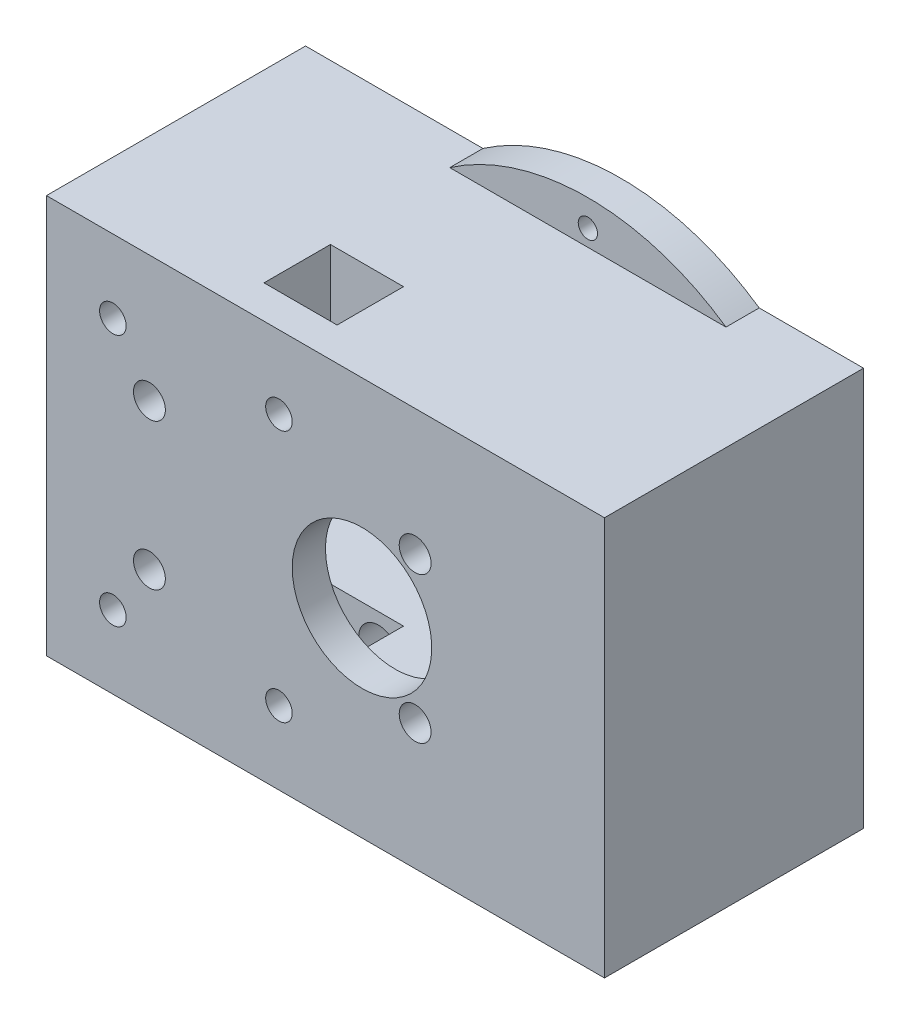
SolidWorks part; units mm, degrees
ref_plane "前视基准面" through (0, 0, 0) normal (0, 0, 1) x (1, 0, 0)
ref_plane "上视基准面" through (0, 0, 0) normal (0, 1, 0) x (1, 0, 0)
ref_plane "右视基准面" through (0, 0, 0) normal (1, 0, 0) x (0, 0, -1)
sketch "草图1" plane through (0, 0, 0) normal (0, 0, 1) x (1, 0, 0)
  line L1 (-33.4499, 20.5621) -> (50.5501, 20.5621)
  line L2 (-33.4499, 20.5621) -> (-33.4499, -39.4379)
  line L3 (-33.4499, -39.4379) -> (50.5501, -39.4379)
  line L4 (50.5501, 20.5621) -> (50.5501, -39.4379)
  dimension "D1" = 84
  dimension "D2" = 60
extrude "凸台-拉伸1" add sketch "草图1" along normal blind 39
sketch "草图3" plane through (0, 0, 0) normal (0, 0, -1) x (-1, 0, 0)
  line L1 (-50.5501, -39.4379) -> (-50.5501, 20.5621) construction
  line L2 (33.4499, -39.4379) -> (-50.5501, -39.4379) construction
  circle A0 centre (-14.0501, -9.4379) radius 36.5
  point P2 (-21.5499, -29.1391)
  dimension "D1" = 36.5
  dimension "D2" = 30
extrude "凸台-拉伸2" add sketch "草图3" against normal blind 5
sketch "草图4" plane through (0, 0, 0) normal (0, 0, -1) x (-1, 0, 0)
  line L0 (-50.5501, -39.4379) -> (-50.5501, 20.5621) construction
  line L1 (-34.8408, -39.4379) -> (-50.5501, -39.4379) construction
  circle A0 centre (-46.5501, -9.4379) radius 1.45
  dimension "D1" = 2.9
  dimension "D2" = 4
  dimension "D3" = 30
extrude "切除-拉伸2" cut sketch "草图4" against normal blind 5
pattern_circular "阵列(圆周)1" count 8 over 360 about axis through (14.0501, -9.4379, 0) along (0, 0, 1) of "切除-拉伸2"
sketch "草图2" plane through (0, 0, 0) normal (0, 0, -1) x (-1, 0, 0)
  line L0 (33.4499, 20.5621) -> (33.4499, -39.4379) construction
  line L1 (33.4499, 4.8121) -> (-25.3001, 4.8121)
  line L2 (33.4499, 4.8121) -> (33.4499, -23.6879)
  line L3 (33.4499, -23.6879) -> (-25.3001, -23.6879)
  line L4 (-25.3001, 4.8121) -> (-25.3001, -23.6879)
  line L5 (-50.5501, 20.5621) -> (-34.8408, 20.5621) construction
  line L6 (33.4499, -39.4379) -> (6.7405, -39.4379) construction
  dimension "D1" = 58.75
  dimension "D2" = 15.75
  dimension "D3" = 15.75
extrude "切除-拉伸1" cut sketch "草图2" against normal blind 34
sketch "草图6" plane through (0, 0, 34) normal (0, 0, -1) x (-1, 0, 0)
  line L1 (-25.3001, -23.6879) -> (33.4499, -23.6879) construction
  line L2 (33.4499, -23.6879) -> (33.4499, 4.8121) construction
  line L3 (33.4499, 4.8121) -> (-25.3001, 4.8121) construction
  line L4 (-25.3001, -23.6879) -> (33.4499, -23.6879) construction
  line L5 (33.4499, 4.8121) -> (-25.3001, 4.8121) construction
  circle A0 centre (-14.0501, -9.4379) radius 10.5
  circle A1 centre (-22.0501, 1.5621) radius 2.4
  circle A2 centre (-22.0501, -20.4379) radius 2.4
  circle A3 centre (17.9499, -20.4379) radius 2.4
  circle A4 centre (17.9499, 1.5621) radius 2.4
  dimension "D1" = 14.25
  dimension "D2" = 47.5
  dimension "D3" = 3.25
  dimension "D4" = 55.5
  dimension "D5" = 3.25
  dimension "D6" = 55.5
  dimension "D7" = 3.25
  dimension "D8" = 15.5
  dimension "D9" = 3.25
  dimension "D10" = 15.5
extrude "切除-拉伸3" cut sketch "草图6" against normal blind 5
sketch "草图7" plane through (0, 0, 39) normal (0, 0, 1) x (1, 0, 0)
  line L0 (50.5501, 20.5621) -> (-33.4499, 20.5621) construction
  line L1 (-33.4499, 20.5621) -> (-33.4499, -39.4379) construction
  line L2 (-33.4499, -39.4379) -> (50.5501, -39.4379) construction
  circle A0 centre (-23.4499, 9.5621) radius 2
  circle A1 centre (-23.4499, -28.4379) radius 2
  circle A2 centre (1.5501, 9.5621) radius 2
  circle A3 centre (1.5501, -28.4379) radius 2
  dimension "D1" = 11
  dimension "D2" = 10
  dimension "D3" = 10
  dimension "D4" = 11
  dimension "D5" = 25
  dimension "D6" = 25
extrude "切除-拉伸4" cut sketch "草图7" against normal blind 40
sketch "草图8" plane through (0, 0, 0) normal (0, 0, -1) x (-1, 0, 0)
  circle A0 centre (-1.5501, 9.5621) radius 3
  circle A1 centre (23.4499, 9.5621) radius 3
  circle A2 centre (-1.5501, -28.4379) radius 3
  circle A3 centre (23.4499, -28.4379) radius 3
extrude "切除-拉伸5" cut sketch "草图8" against normal blind 34
sketch "草图9" plane through (0, -39.4379, 0) normal (0, -1, 0) x (-1, 0, 0)
  line L0 (-50.5501, -39) -> (-50.5501, 0) construction
  line L1 (5.6999, -34) -> (-5.3001, -34)
  line L2 (5.6999, -34) -> (5.6999, -24)
  line L3 (5.6999, -24) -> (-5.3001, -24)
  line L4 (-5.3001, -34) -> (-5.3001, -24)
  line L5 (33.4499, -39) -> (-50.5501, -39) construction
  dimension "D1" = 11
  dimension "D2" = 10
  dimension "D3" = 45.25
  dimension "D4" = 5
extrude "切除-拉伸6" cut sketch "草图9" against normal blind 100
sketch "草图10" plane through (50.5501, 0, 0) normal (1, 0, 0) x (0, 0, -1)
  line L0 (-39, -9.4379) -> (0, -9.4379) construction
  line L3 (-39, -39.4379) -> (-39, 20.5621) construction
  line L4 (0, -39.4379) -> (0, 20.5621) construction
  line L5 (-19.5, 20.5621) -> (-19.5, -39.4379) construction
  line L6 (-39, 20.5621) -> (0, 20.5621) construction
  line L7 (-39, -39.4379) -> (0, -39.4379) construction
  point P12 (-19.5, -9.4379)
  point P13 (0, 0)
